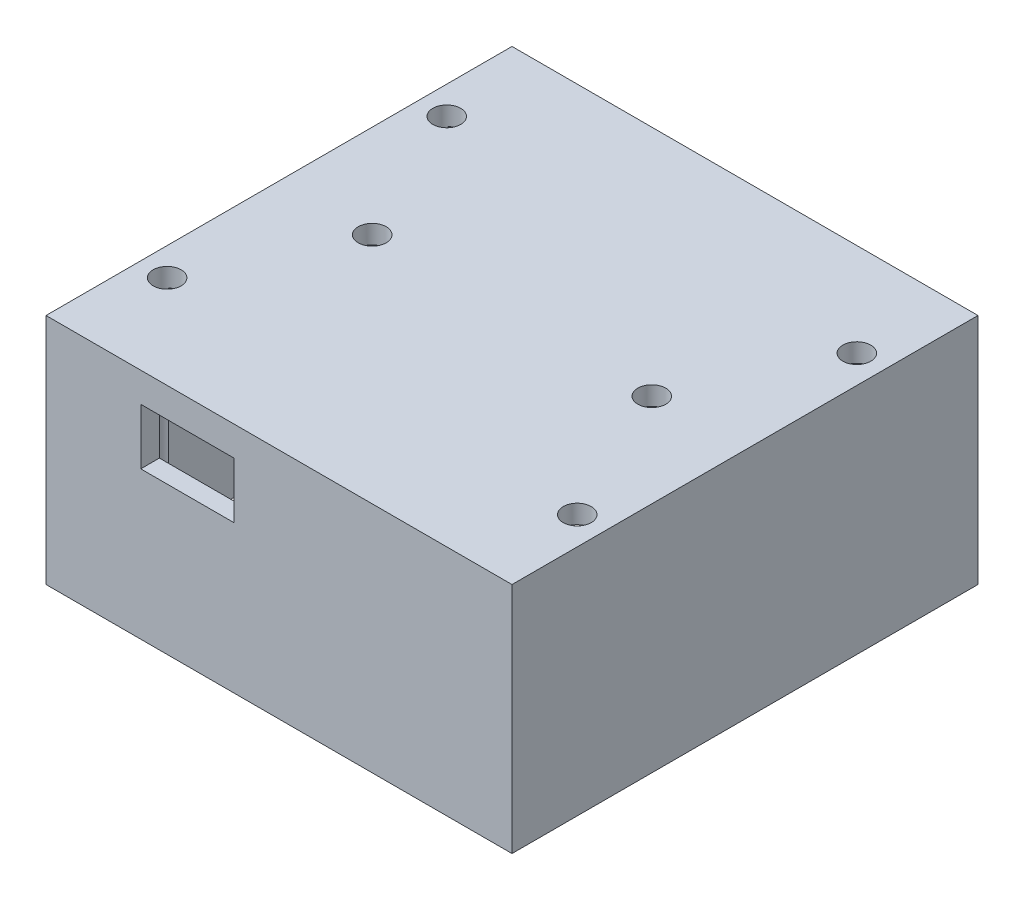
SolidWorks part; units mm, degrees
material "ABS"
ref_plane "Front Plane" through (0, 0, 0) normal (0, 0, 1) x (1, 0, 0)
ref_plane "Top Plane" through (0, 0, 0) normal (0, 1, 0) x (1, 0, 0)
ref_plane "Right Plane" through (0, 0, 0) normal (1, 0, 0) x (0, 0, -1)
sketch "Sketch1" plane through (0, 0, 0) normal (0, 1, 0) x (1, 0, 0)
  line L0 (-25, 25) -> (25, 25)
  line L1 (-25, 25) -> (-25, -25)
  line L2 (-25, -25) -> (25, -25)
  line L3 (25, 25) -> (25, -25)
  line L4 (-25, 25) -> (25, -25) construction
  line L5 (-25, -25) -> (25, 25) construction
  point P0 (0, 0)
extrude "Boss-Extrude1" add sketch "Sketch1" along normal blind 25
sketch "Sketch2" plane through (0, 25, 0) normal (0, 1, 0) x (1, 0, 0)
  line L0 (0, 34.6867) -> (0, -34.6867) construction
  line L1 (-44.6063, 0) -> (44.6063, 0) construction
  line L2 (25, -25) -> (25, 25) construction
  line L3 (-25, 25) -> (-25, -25) construction
  line L4 (25, 25) -> (-25, 25) construction
  circle A0 centre (15, 0) radius 1.5
  circle A1 centre (-15, 0) radius 1.5
  circle A2 centre (-22, 15) radius 1.5
  circle A3 centre (22, 15) radius 1.5
  circle A4 centre (22, -15) radius 1.5
  circle A5 centre (-22, -15) radius 1.5
  point P4 (0, 0)
  point P8 (0, 0)
  dimension "D2" = 3
  dimension "D3" = 3
  dimension "D4" = 3
  dimension "D1" = 10
  dimension "D5" = 10
sketch "Sketch3" plane through (0, 0, 25) normal (0, 0, 1) x (1, 0, 0)
  line L1 (-14.8336, 21.8318) -> (-4.8336, 21.8318)
  line L2 (-14.8336, 21.8318) -> (-14.8336, 15.8318)
  line L3 (-14.8336, 15.8318) -> (-4.8336, 15.8318)
  line L4 (-4.8336, 21.8318) -> (-4.8336, 15.8318)
  line L5 (-14.8336, 21.8318) -> (-4.8336, 15.8318) construction
  line L6 (-14.8336, 15.8318) -> (-4.8336, 21.8318) construction
  point P0 (-9.8336, 18.8318)
  dimension "D1" = 10
  dimension "D2" = 6
shell "Shell1" thickness 2
extrude "Cut-Extrude1" cut sketch "Sketch3" against normal blind 12
extrude "Cut-Extrude2" cut sketch "Sketch2" against normal through all
